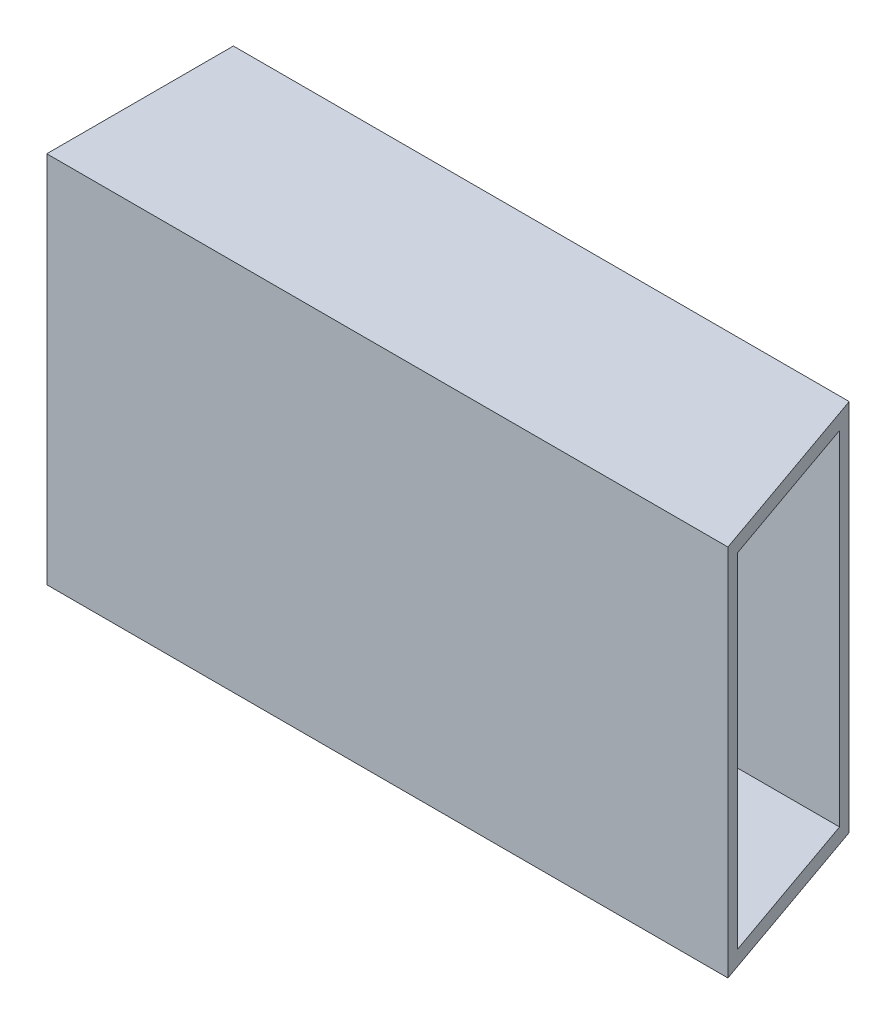
SolidWorks part; units mm, degrees
ref_plane "Płaszczyzna przednia" through (0, 0, 0) normal (0, 0, 1) x (1, 0, 0)
ref_plane "Płaszczyzna górna" through (0, 0, 0) normal (0, 1, 0) x (1, 0, 0)
ref_plane "Płaszczyzna prawa" through (0, 0, 0) normal (1, 0, 0) x (0, 0, -1)
sketch "Szkic1" plane through (0, 0, 0) normal (0, 1, 0) x (1, 0, 0)
  line L0 (0, 0) -> (182.5, 0)
  line L1 (182.5, 0) -> (165, 50)
  line L2 (165, 50) -> (0, 50)
  line L3 (0, 50) -> (0, 0)
  dimension "D1" = 182.5
  dimension "D2" = 165
  dimension "D3" = 50
extrude "Dodanie-wyciągnięcie1" add sketch "Szkic1" along normal blind 100
sketch "Szkic2" plane through (0, 0, 0) normal (-1, 0, 0) x (0, 0, 1)
  line L0 (-46, 4) -> (-4, 4)
  line L1 (-4, 4) -> (-4, 96)
  line L2 (-4, 96) -> (-46, 96)
  line L3 (-46, 96) -> (-46, 4)
  line L4 (-50, 0) -> (0, 0) construction
  line L5 (-50, 100) -> (0, 100) construction
  line L6 (0, 100) -> (0, 0) construction
  line L7 (-50, 100) -> (-50, 0) construction
  dimension "D1" = 4
  dimension "D2" = 4
  dimension "D3" = 4
  dimension "D4" = 4
extrude "Wytnij-wyciągnięcie1" cut sketch "Szkic2" against normal blind 200
